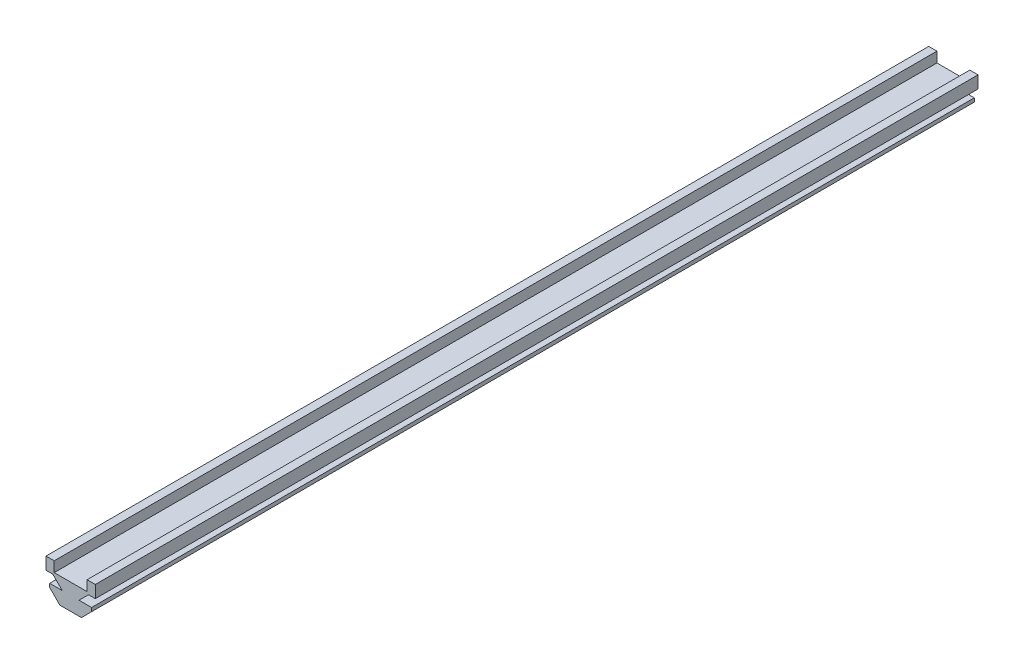
SolidWorks part; units mm, degrees
ref_plane "Alzado" through (0, 0, 0) normal (0, 0, 1) x (1, 0, 0)
ref_plane "Planta" through (0, 0, 0) normal (0, 1, 0) x (1, 0, 0)
ref_plane "Vista lateral" through (0, 0, 0) normal (1, 0, 0) x (0, 0, -1)
sketch "Croquis1" plane through (0, 0, 0) normal (0, 0, 1) x (1, 0, 0)
  line L0 (12.6279, -5.675) -> (15.1, -3.2029)
  line L8 (7.1649, -6.175) -> (10, -6.175)
  line L9 (15.1, -2.3) -> (15.1, -3.2029)
  line L10 (15.1, -2.3) -> (12.0429, -2.3)
  line L12 (7.3721, -5.675) -> (12.6279, -5.675)
  line L13 (10, -6.175) -> (10, 0.5) construction
  line L33 (7.3721, -5.675) -> (4.9, -3.2029)
  line L34 (4.9, -2.3) -> (4.9, -3.2029)
  line L35 (4.9, -2.3) -> (7.9571, -2.3)
  line L41 (12.0429, -2.3) -> (14.3429, 0)
  line L42 (7.9571, -2.3) -> (5.6571, 0)
  line L43 (14.3429, 0) -> (16, 0)
  line L49 (16, 0) -> (16, 3)
  line L50 (14, 3) -> (16, 3)
  line L51 (10, 0.5) -> (10, -6.175)
  line L54 (6, 0.5) -> (14, 0.5)
  line L56 (14, 0.5) -> (14, 3)
  line L62 (5.6571, 0) -> (4, 0)
  line L65 (7.1649, -6.175) -> (4.4, -3.4101)
  line L66 (4.4, -1.8) -> (4.4, -3.4101)
  line L67 (4.4, -1.8) -> (6.75, -1.8)
  line L68 (6.75, -1.8) -> (4.95, 0)
  line L69 (0, 0) -> (4.4, 0)
  line L70 (4.4, 0) -> (4.95, 0)
  line L75 (6, 0.5) -> (6, 3)
  line L76 (6, 3) -> (4, 3)
  line L77 (4, 0) -> (4, 3)
  line L89 (10, 0.5) -> (6, 0.5)
  point P3 (10, -5.675)
  dimension "D1" = 10
  dimension "D2" = 4
  dimension "D5" = 2
  dimension "D4" = 3
  dimension "D6" = 0.5
extrude "Saliente-Extruir1" add sketch "Croquis1" along normal blind 215 contours L77 L62 L42 L35 L34 L33 L12 L51 L54 L75 L76 | L56 L54 L51 L12 L0 L9 L10 L41 L43 L49 L50
